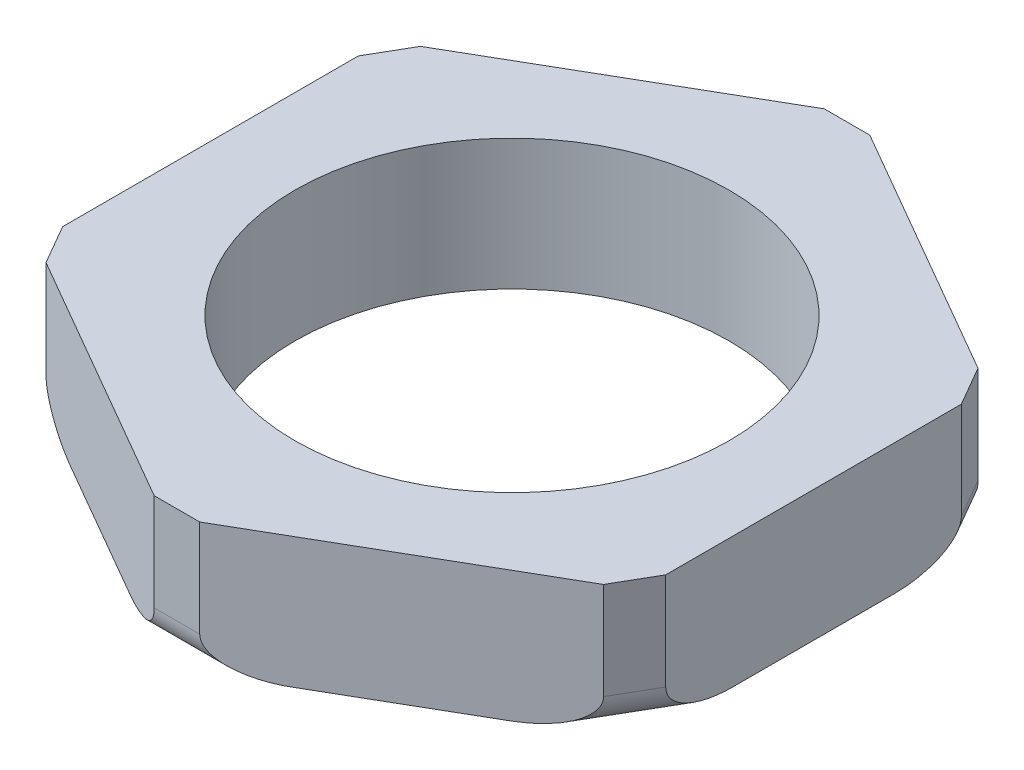
SolidWorks part; units mm, degrees
ref_plane "Спереди (Плоскость XY)" through (0, 0, 0) normal (0, 0, 1) x (1, 0, 0)
ref_plane "Сверху (Плоскость XZ)" through (0, 0, 0) normal (0, 1, 0) x (1, 0, 0)
ref_plane "Справа (Плоскость ZY)" through (0, 0, 0) normal (1, 0, 0) x (0, 0, -1)
sketch "Эскиз1" plane through (0, 0, 0) normal (0, 1, 0) x (1, 0, 0)
  line L0 (0.6795, 10) -> (8.3205, 5.5885)
  line L1 (9, 4.4115) -> (9, -4.4115)
  line L2 (8.3205, -5.5885) -> (0.6795, -10)
  line L3 (-0.6795, -10) -> (-8.3205, -5.5885)
  line L4 (-9, -4.4115) -> (-9, 4.4115)
  line L5 (-8.3205, 5.5885) -> (-0.6795, 10)
  line L6 (-9, 4.4115) -> (-8.3205, 5.5885)
  line L7 (-8.6603, 5) -> (8.6603, -5) construction
  line L8 (0, 0) -> (7.4866, 12.9671) construction
  line L9 (8.3205, -5.5885) -> (9, -4.4115)
  line L10 (-0.6795, 10) -> (0.6795, 10)
  line L11 (8.3205, 5.5885) -> (9, 4.4115)
  line L12 (9, -4.4115) -> (8.3205, -5.5885)
  line L13 (0.6795, -10) -> (-0.6795, -10)
  line L14 (-8.3205, -5.5885) -> (-9, -4.4115)
  circle A0 centre (0, 0) radius 6.48
  point P13 (0, 0)
  point P34 (0, 0)
  dimension "D1" = 12.96
  dimension "D2" = 18
  dimension "D3" = 20
extrude "Бобышка-Вытянуть1" add sketch "Эскиз1" along normal blind 3.9
fillet "Скругление1" radius 1 6 edges at (-8.6603, 0, -5) (-8.6603, 0, 5) (0, 0, 10) (8.6603, 0, 5) (8.6603, 0, -5) (0, 0, -10)
